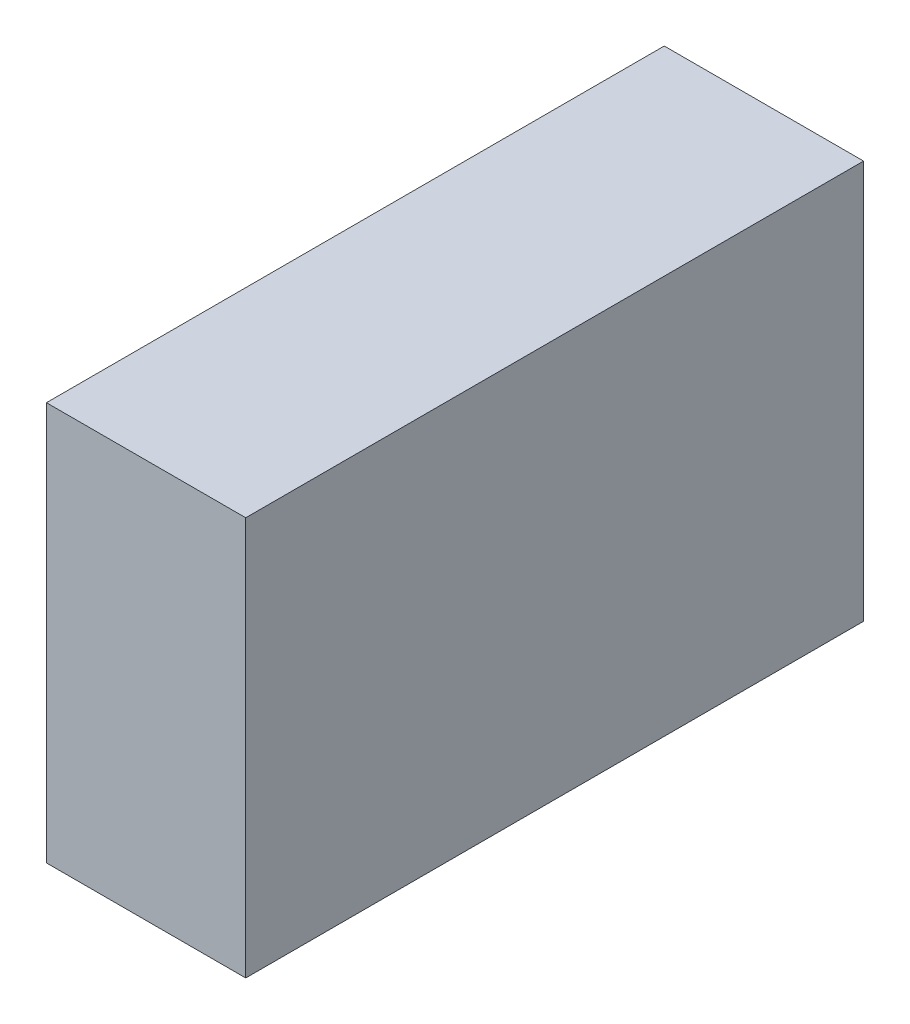
SolidWorks part; units mm, degrees
ref_plane "Front Plane" through (0, 0, 0) normal (0, 0, 1) x (1, 0, 0)
ref_plane "Top Plane" through (0, 0, 0) normal (0, 1, 0) x (1, 0, 0)
ref_plane "Right Plane" through (0, 0, 0) normal (1, 0, 0) x (0, 0, -1)
sketch "Sketch1" plane through (0, 0, 0) normal (1, 0, 0) x (0, 0, -1)
  line L1 (0, 0) -> (31, 0)
  line L2 (0, 0) -> (0, 20)
  line L3 (0, 20) -> (31, 20)
  line L4 (31, 0) -> (31, 20)
extrude "Boss-Extrude1" add sketch "Sketch1" against normal blind 10
